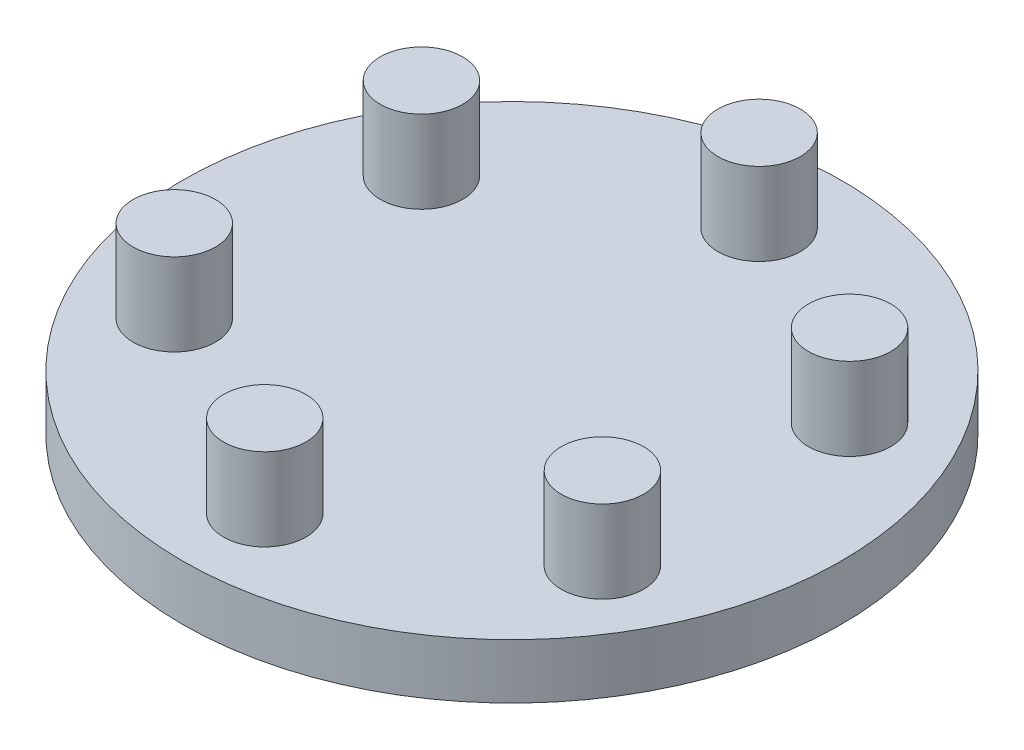
SolidWorks part; units mm, degrees
ref_plane "Plan de face" through (0, 0, 0) normal (0, 0, 1) x (1, 0, 0)
ref_plane "Plan de dessus" through (0, 0, 0) normal (0, 1, 0) x (1, 0, 0)
ref_plane "Plan de droite" through (0, 0, 0) normal (1, 0, 0) x (0, 0, -1)
sketch "Esquisse1" plane through (0, 0, 0) normal (0, 1, 0) x (1, 0, 0)
  circle A0 centre (0, 0) radius 60
  dimension "D1" = 120
extrude "Boss.-Extru.1" add sketch "Esquisse1" along normal blind 10 contours A0
sketch "Esquisse2" plane through (0, 10, 0) normal (0, 1, 0) x (1, 0, 0)
  circle A0 centre (0, 45) radius 7.5
  dimension "D2" = 15
  dimension "D1" = 45
extrude "Boss.-Extru.2" add sketch "Esquisse2" along normal blind 15
pattern_circular "Répétition circulaire1" count 6 every 60 about axis through (0, 0, 0) along (0, 1, 0) of "Boss.-Extru.2"
